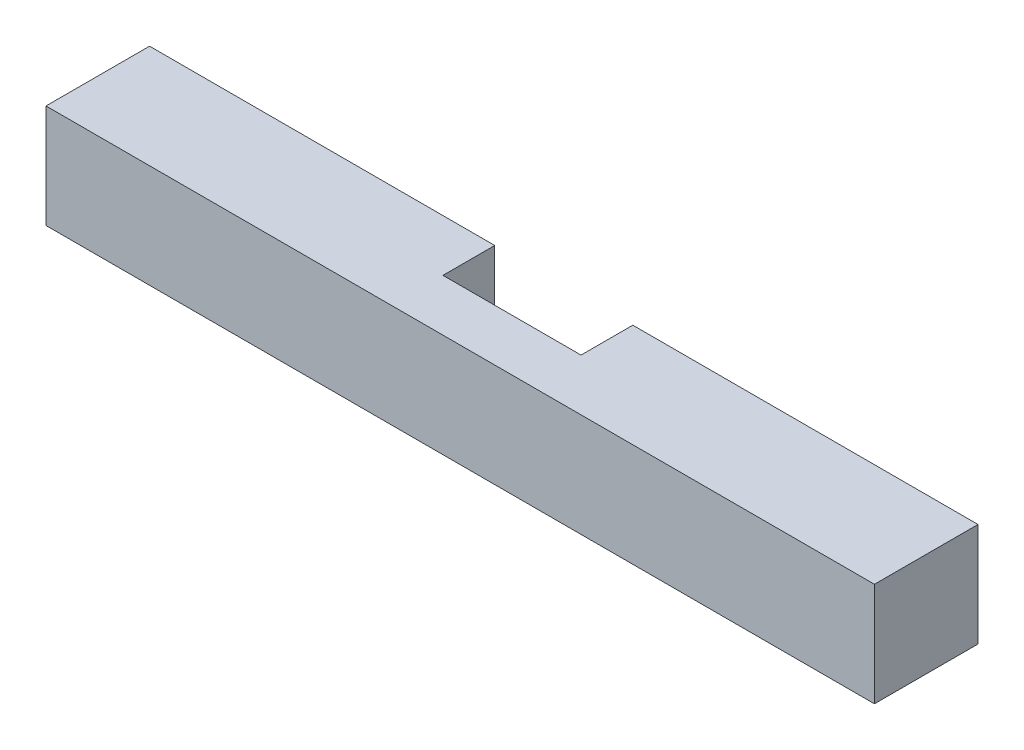
SolidWorks part; units mm, degrees
ref_plane "Front Plane" through (0, 0, 0) normal (0, 0, 1) x (1, 0, 0)
ref_plane "Top Plane" through (0, 0, 0) normal (0, 1, 0) x (1, 0, 0)
ref_plane "Right Plane" through (0, 0, 0) normal (1, 0, 0) x (0, 0, -1)
sketch "Sketch1" plane through (0, 0, 0) normal (0, 1, 0) x (1, 0, 0)
  line L0 (0, 0) -> (50.8, 0)
  line L1 (50.8, 0) -> (50.8, 6.35)
  line L2 (50.8, 6.35) -> (29.6333, 6.35)
  line L3 (29.6333, 6.35) -> (29.6333, 3.175)
  line L4 (29.6333, 3.175) -> (21.1667, 3.175)
  line L5 (21.1667, 3.175) -> (21.1667, 6.35)
  line L6 (21.1667, 6.35) -> (0, 6.35)
  line L7 (0, 6.35) -> (0, 0)
  dimension "D1" = 50.8
  dimension "D2" = 21.1667
  dimension "D3" = 3.175
  dimension "D4" = 8.4667
  dimension "D5" = 6.35
  dimension "D6" = 6.35
extrude "Boss-Extrude1" add sketch "Sketch1" along normal blind 6.35
